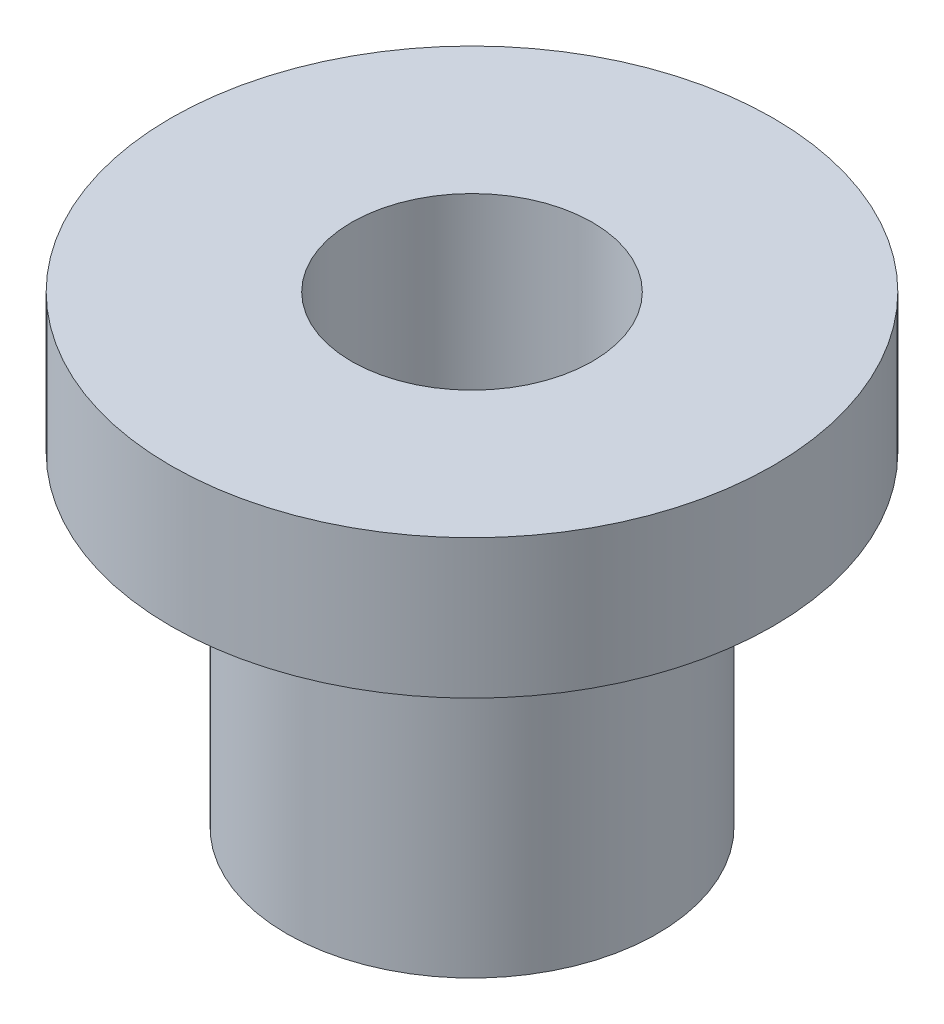
SolidWorks part; units mm, degrees
ref_plane "Front Plane" through (0, 0, 0) normal (0, 0, 1) x (1, 0, 0)
ref_plane "Top Plane" through (0, 0, 0) normal (0, 1, 0) x (1, 0, 0)
ref_plane "Right Plane" through (0, 0, 0) normal (1, 0, 0) x (0, 0, -1)
sketch "Sketch1" plane through (0, 0, 0) normal (0, 1, 0) x (1, 0, 0)
  circle A0 centre (0, 0) radius 4
  circle A1 centre (0, 0) radius 2.6
  dimension "D1" = 5.2
  dimension "D2" = 8
extrude "Boss-Extrude1" add sketch "Sketch1" along normal blind 7
sketch "Sketch2" plane through (0, 7, 0) normal (0, 1, 0) x (1, 0, 0)
  circle A0 centre (0, 0) radius 2.6
  circle A1 centre (0, 0) radius 6.5
  dimension "D1" = 13
extrude "Boss-Extrude2" add sketch "Sketch2" along normal blind 3
